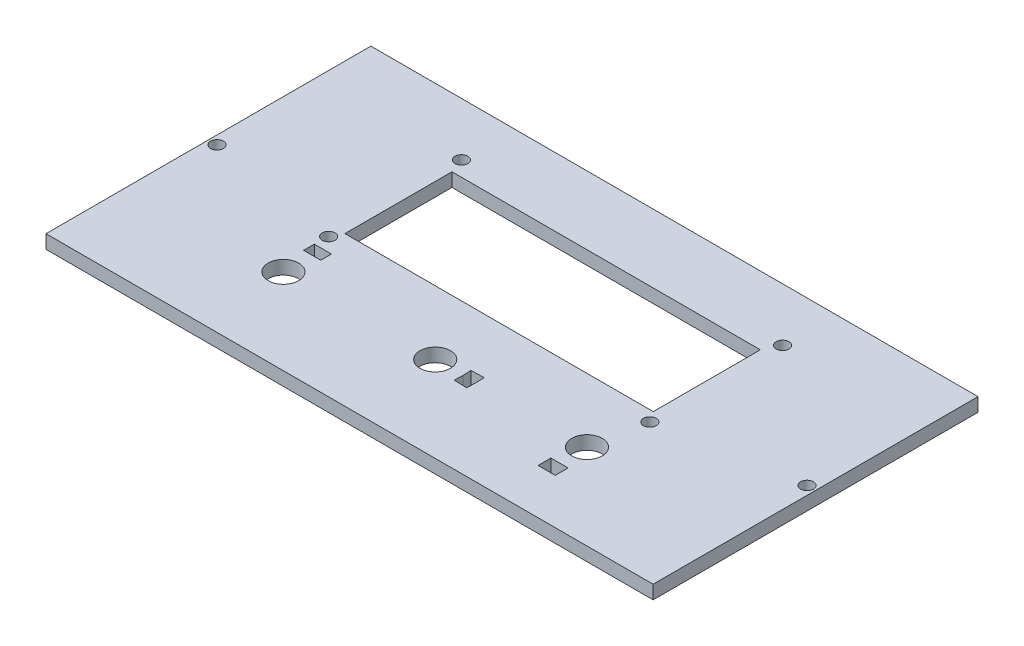
SolidWorks part; units mm, degrees
ref_plane "Front Plane" through (0, 0, 0) normal (0, 0, 1) x (1, 0, 0)
ref_plane "Top Plane" through (0, 0, 0) normal (0, 1, 0) x (1, 0, 0)
ref_plane "Right Plane" through (0, 0, 0) normal (1, 0, 0) x (0, 0, -1)
sketch "Sketch1" plane through (0, 0, 0) normal (0, 1, 0) x (1, 0, 0)
  line L0 (-0.5607, -4.2524) -> (-0.5607, 13.9302) construction
  line L1 (-70.8808, 37.9292) -> (70.8808, 37.9292)
  line L2 (-70.8808, 37.9292) -> (-70.8808, -37.9292)
  line L3 (-70.8808, -37.9292) -> (70.8808, -37.9292)
  line L4 (70.8808, 37.9292) -> (70.8808, -37.9292)
  line L5 (-70.8808, 37.9292) -> (70.8808, -37.9292) construction
  line L6 (-70.8808, -37.9292) -> (70.8808, 37.9292) construction
  line L7 (-38.0536, -3.5217) -> (36.9322, -4.9831) construction
  line L8 (26.0322, 13.9302) -> (-35.413, 13.9302) construction
  line L10 (-35.2377, 22.9285) -> (-35.5884, 4.9319) construction
  point P0 (0, 0)
  dimension "D1" = 141.7616
  dimension "D2" = 75.8584
extrude "Boss-Extrude1" add sketch "Sketch1" along normal blind 3.175
sketch "Sketch2" plane through (0, 3.175, 0) normal (0, 1, 0) x (1, 0, 0)
  line L0 (-70.8808, -17.9292) -> (70.8808, -17.9292) construction
  line L1 (-70.8808, 37.9292) -> (-70.8808, -37.9292) construction
  line L2 (70.8808, -37.9292) -> (70.8808, 37.9292) construction
  line L3 (0, 37.9292) -> (0, -37.9292) construction
  line L4 (70.8808, 37.9292) -> (-70.8808, 37.9292) construction
  line L5 (-70.8808, -37.9292) -> (70.8808, -37.9292) construction
  circle A1 centre (-35.4408, -17.9292) radius 3.5625
  circle A2 centre (0, -17.9292) radius 3.5625
  circle A3 centre (35.4408, -17.9292) radius 3.5625
  dimension "D2" = 7.125
  dimension "D3" = 7.125
  dimension "D4" = 7.125
  dimension "D1" = 20
  dimension "D5" = 35.44
  dimension "D6" = 35.44
extrude "Cut-Extrude1" cut sketch "Sketch2" against normal blind 10
sketch "Sketch3" plane through (0, 3.175, 0) normal (0, 1, 0) x (1, 0, 0)
  line L0 (0, 37.9292) -> (0, -37.9292) construction
  line L1 (70.8808, 37.9292) -> (-70.8808, 37.9292) construction
  line L2 (-70.8808, -37.9292) -> (70.8808, -37.9292) construction
  line L3 (-70.8808, 0) -> (0, 0) construction
  line L4 (-70.8808, 37.9292) -> (-70.8808, -37.9292) construction
  line L6 (-36, 21.985) -> (-36, -3.015)
  line L7 (-70.8808, 9.485) -> (0, 9.485) construction
  line L8 (-36, -3.015) -> (36, -3.015)
  line L10 (36, 21.985) -> (-36, 21.985)
  line L15 (36, 21.985) -> (36, -3.015)
  dimension "D1" = 25
  dimension "D2" = 9.485
  dimension "D3" = 72
extrude "Cut-Extrude2" cut sketch "Sketch3" against normal blind 10
sketch "Sketch4" plane through (0, 3.175, 0) normal (0, 1, 0) x (1, 0, 0)
  circle A0 centre (37.7, 25.485) radius 1.5
  circle A1 centre (37.7, -5.515) radius 1.5
  circle A2 centre (-37.3, -5.515) radius 1.5
  circle A3 centre (-37.3, 25.485) radius 1.5
  dimension "D1" = 3
  dimension "D2" = 3
  dimension "D3" = 3
  dimension "D4" = 3
extrude "Cut-Extrude3" cut sketch "Sketch4" against normal blind 10
sketch "Sketch5" plane through (0, 3.175, 0) normal (0, 1, 0) x (1, 0, 0)
  line L0 (70.8808, 0) -> (-70.8808, 0) construction
  line L1 (70.8808, -37.9292) -> (70.8808, 37.9292) construction
  line L2 (-70.8808, 37.9292) -> (-70.8808, -37.9292) construction
  circle A0 centre (68.8808, 0) radius 1.5
  circle A1 centre (-68.8808, 0) radius 1.5
  dimension "D1" = 3
  dimension "D3" = 3
  dimension "D2" = 2
  dimension "D4" = 2
extrude "Cut-Extrude4" cut sketch "Sketch5" against normal blind 10
sketch "Sketch7" plane through (0, 0, 0) normal (0, -1, 0) x (1, 0, 0)
  line L0 (-35.4408, 10.5216) -> (-35.4408, 9.4292) construction
  line L1 (-36.4908, 10.5216) -> (-34.3908, 10.5216) construction
  line L2 (-35.4408, 9.9754) -> (-36.6908, 9.9754) construction
  line L3 (-35.4408, 11.2254) -> (-37.4408, 11.2254)
  line L4 (-35.4408, 8.7254) -> (-33.4408, 8.7254)
  line L5 (-36.6908, 9.6959) -> (-36.6908, 10.3216) construction
  line L6 (-35.4408, 8.7254) -> (-37.4408, 8.7254)
  line L7 (-37.4408, 11.2254) -> (-37.4408, 8.7254)
  line L8 (-33.4408, 11.2254) -> (-33.4408, 8.7254)
  line L9 (-35.4408, 11.2254) -> (-33.4408, 11.2254)
  line L10 (7.4076, 17.9292) -> (8.5, 17.9292) construction
  line L11 (7.4076, 16.8792) -> (7.4076, 18.9792) construction
  line L12 (7.9205, 19.1792) -> (7.9538, 17.9292) construction
  line L13 (8.2333, 19.1792) -> (7.6076, 19.1792) construction
  line L14 (6.401, 19.8892) -> (9.3999, 19.9692)
  line L15 (9.3999, 19.9692) -> (9.4543, 17.9292)
  line L16 (6.401, 19.8892) -> (6.4554, 17.8492)
  line L17 (9.3999, 15.8892) -> (9.4543, 17.9292)
  line L18 (6.401, 15.9692) -> (9.3999, 15.8892)
  line L19 (6.401, 15.9692) -> (6.4554, 18.0092)
  line L20 (-35.4408, 11.2254) -> (-35.4408, 8.7254) construction
  line L21 (34.1908, 25.8497) -> (36.6908, 25.8497) construction
  line L22 (34.1908, 26.1625) -> (34.1908, 25.5368) construction
  line L23 (36.6908, 26.1625) -> (36.6908, 25.5368) construction
  line L24 (35.4408, 25.8497) -> (35.4408, 26.5688) construction
  line L25 (37.4408, 27.3497) -> (33.4408, 27.3497)
  line L26 (33.4408, 27.3497) -> (33.4408, 24.3497)
  line L27 (37.4408, 24.3497) -> (33.4408, 24.3497)
  line L28 (37.4408, 27.3497) -> (37.4408, 24.3497)
  circle A0 centre (-35.4408, 17.9292) radius 8.5 construction
  circle A1 centre (0, 17.9292) radius 8.5 construction
  point P18 (-37.4408, 9.9754)
  point P36 (7.9004, 19.9292)
  point P50 (33.4408, 25.8497)
  point P51 (35.4408, 24.3497)
  point P52 (35.4408, 27.3497)
  dimension "D1" = 2
  dimension "D2" = 1.25
  dimension "D3" = 1.5
  dimension "D4" = 2
  dimension "D5" = 2
  dimension "D6" = 1.5
extrude "Cut-Extrude5" cut sketch "Sketch7" against normal blind 10
